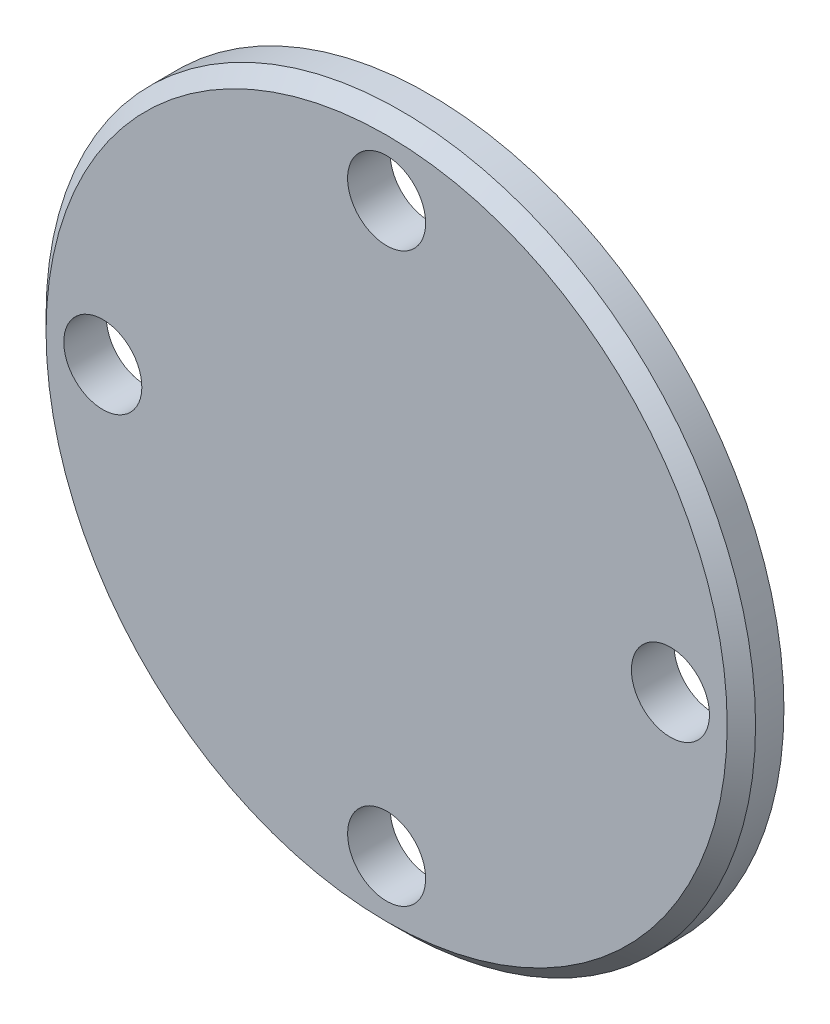
SolidWorks part; units mm, degrees
ref_plane "前视基准面" through (0, 0, 0) normal (0, 0, 1) x (1, 0, 0)
ref_plane "上视基准面" through (0, 0, 0) normal (0, 1, 0) x (1, 0, 0)
ref_plane "右视基准面" through (0, 0, 0) normal (1, 0, 0) x (0, 0, -1)
sketch "草图1" plane through (0, 0, 0) normal (0, 0, 1) x (1, 0, 0)
  circle A0 centre (0, 0) radius 25
  dimension "D1" = 50
extrude "凸台-拉伸1" add sketch "草图1" along normal blind 3
chamfer "倒角1" distance 1 angle 45 1 edges at (25, 0, 3)
sketch "草图2" plane through (0, 0, 3) normal (0, 0, 1) x (1, 0, 0)
  line L0 (0, -1.65) -> (0, 1.65) construction
  line L1 (1.65, 0) -> (-1.65, 0) construction
  circle A0 centre (0, 20) radius 2.75
  dimension "D1" = 5.5
  dimension "D2" = 20
extrude "切除-拉伸1" cut sketch "草图2" against normal through all
pattern_circular "阵列(圆周)1" count 4 over 360 about axis through (0, 0, 0) along (0, 0, 1) of "切除-拉伸1"
